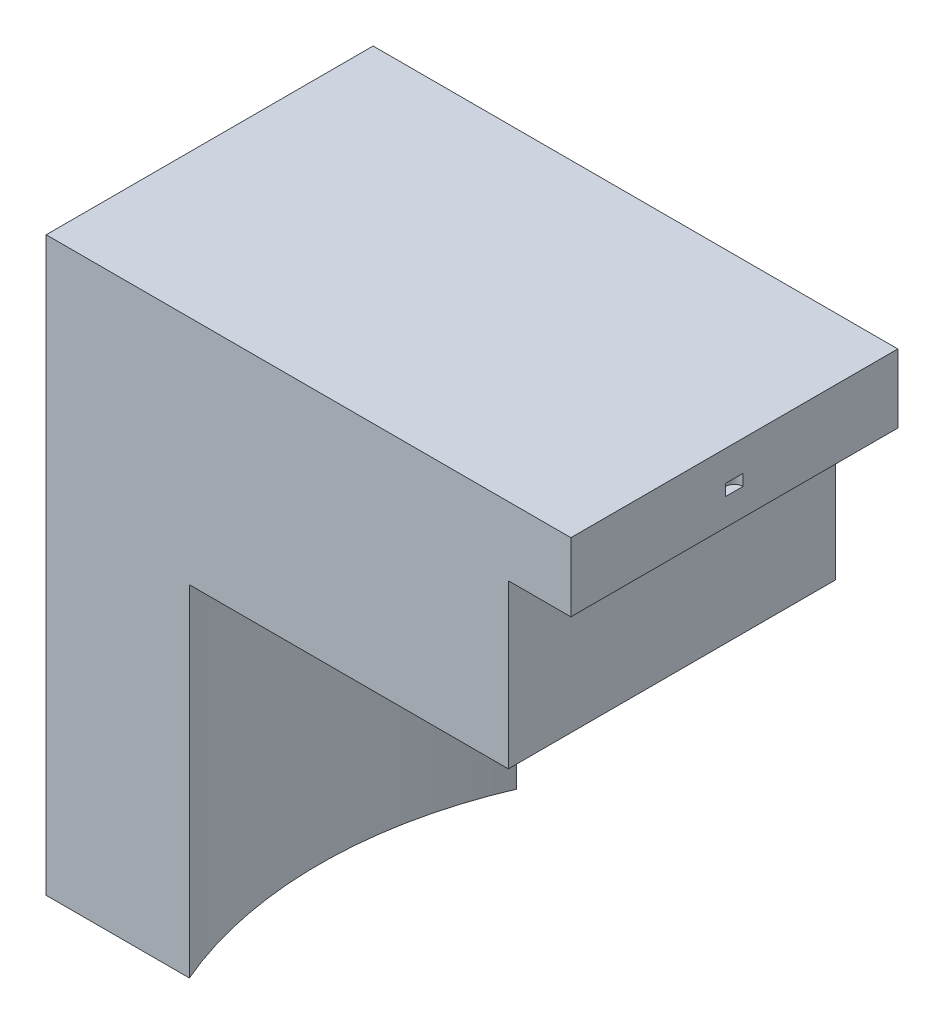
SolidWorks part; units mm, degrees
ref_plane "Front Plane" through (0, 0, 0) normal (0, 0, 1) x (1, 0, 0)
ref_plane "Top Plane" through (0, 0, 0) normal (0, 1, 0) x (1, 0, 0)
ref_plane "Right Plane" through (0, 0, 0) normal (1, 0, 0) x (0, 0, -1)
sketch "Sketch2" plane through (0, 0, 0) normal (0, 0, 1) x (1, 0, 0)
  line L0 (0, 3.1663) -> (-8.153, 3.1663)
  line L1 (-8.153, 3.1663) -> (-8.153, -5.7237)
  line L2 (-8.153, -5.7237) -> (0, -5.7237)
  line L3 (-0.9718, -0.4308) -> (-0.9718, 2.101)
  line L4 (-0.9718, 2.101) -> (0, 2.101)
  line L5 (0, 2.101) -> (0, 3.1663)
  line L10 (0, 5.3642) -> (0, -0.4308) construction
  line L11 (-0.9718, -0.4308) -> (0, -0.4308)
  line L12 (0, -0.4308) -> (0, -5.7237)
  point P2 (0, 0)
  dimension "D3" = 8.89
extrude "Boss-Extrude1" add sketch "Sketch2" along normal mid plane 5.08
sketch "Sketch4" plane through (0, 0, 0) normal (0, 0, 1) x (1, 0, 0)
  line L0 (0, 5.644) -> (0, -8.8945) construction
  line L1 (0, 2.6951) -> (-0.135, 2.6951)
  line L2 (-0.135, 2.6951) -> (-0.135, 2.5182)
  line L3 (-0.135, 2.5182) -> (0, 2.5182)
  line L4 (0, -0.4308) -> (-6.45, -0.4308)
  line L5 (-6.45, -0.4308) -> (-6.45, -5.7914)
  line L6 (-6.45, -5.7914) -> (0, -5.7914)
  line L7 (0, -0.4308) -> (0, -5.7914)
  line L8 (0, 2.6951) -> (0, 2.5182)
  line L9 (0, -0.4308) -> (-0.9718, -0.4308) construction
  dimension "D1" = 0.27
  dimension "D2" = 12.9
revolve "Cut-Revolve2" cut sketch "Sketch4" angle 360 about L0
